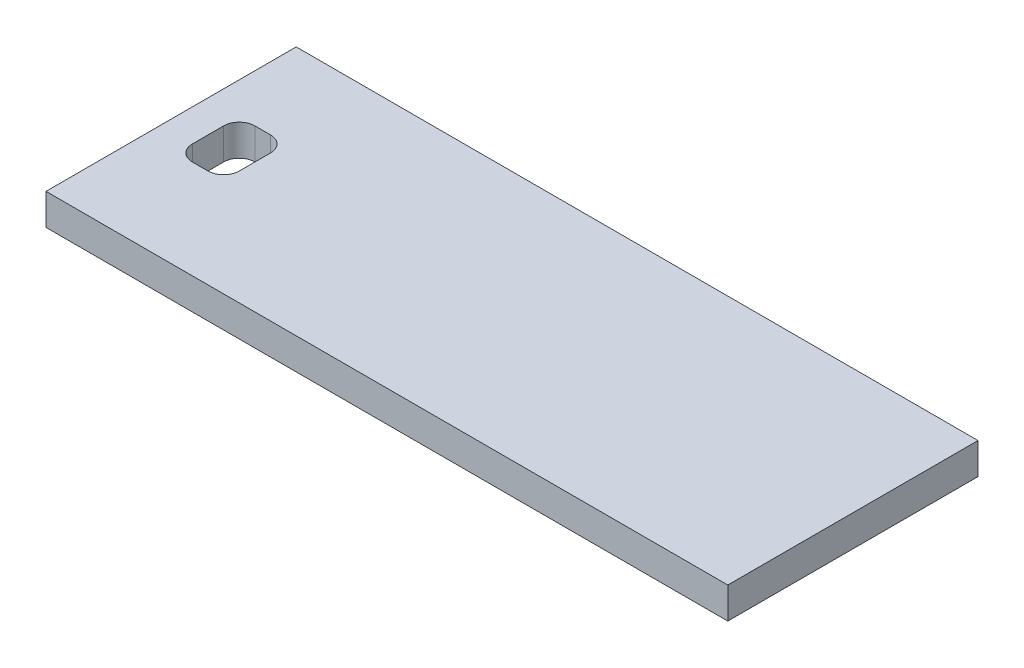
SolidWorks part; units mm, degrees
ref_plane "前视基准面" through (0, 0, 0) normal (0, 0, 1) x (1, 0, 0)
ref_plane "上视基准面" through (0, 0, 0) normal (0, 1, 0) x (1, 0, 0)
ref_plane "右视基准面" through (0, 0, 0) normal (1, 0, 0) x (0, 0, -1)
sketch "草图1" plane through (0, 0, 0) normal (0, 1, 0) x (1, 0, 0)
  line L1 (-109, 40) -> (109, 40)
  line L2 (-109, 40) -> (-109, -40)
  line L3 (-109, -40) -> (109, -40)
  line L4 (109, 40) -> (109, -40)
  line L5 (-109, 40) -> (109, -40) construction
  line L6 (-109, -40) -> (109, 40) construction
  point P0 (0, 0)
  dimension "D1" = 218
  dimension "D2" = 80
extrude "凸台-拉伸1" add sketch "草图1" along normal blind 10
sketch "草图2" plane through (0, 10, 0) normal (0, 1, 0) x (1, 0, 0)
  line L1 (-83.7348, -8.4712) -> (-98.7348, -8.4712)
  line L2 (-83.7348, -8.4712) -> (-83.7348, 11.5288)
  line L3 (-83.7348, 11.5288) -> (-98.7348, 11.5288)
  line L4 (-98.7348, -8.4712) -> (-98.7348, 11.5288)
  line L5 (-83.7348, -8.4712) -> (-98.7348, 11.5288) construction
  line L6 (-83.7348, 11.5288) -> (-98.7348, -8.4712) construction
  point P0 (-91.2348, 1.5288)
  dimension "D1" = 15
  dimension "D2" = 20
extrude "切除-拉伸1" cut sketch "草图2" against normal through all
fillet "圆角1" radius 5 4 edges at (-98.7348, 5, 8.4712) (-83.7348, 5, 8.4712) (-83.7348, 5, -11.5288) (-98.7348, 5, -11.5288)
